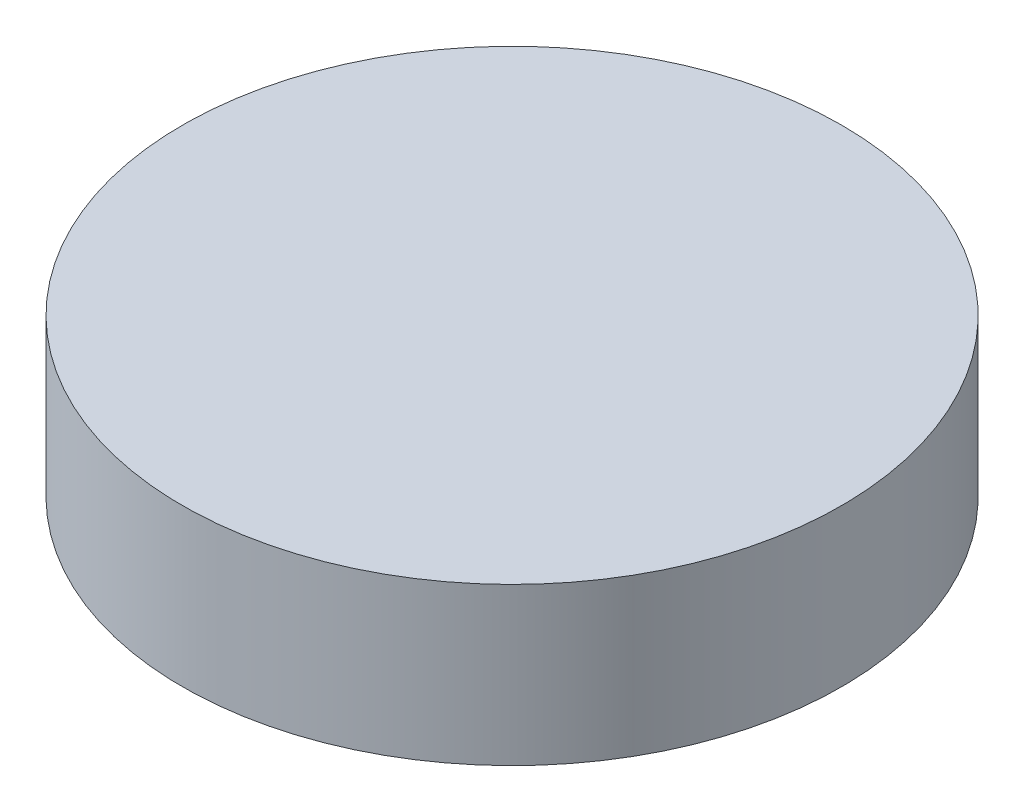
SolidWorks part; units mm, degrees
ref_plane "前视基准面" through (0, 0, 0) normal (0, 0, 1) x (1, 0, 0)
ref_plane "上视基准面" through (0, 0, 0) normal (0, 1, 0) x (1, 0, 0)
ref_plane "右视基准面" through (0, 0, 0) normal (1, 0, 0) x (0, 0, -1)
other "Configuration Table"
sketch "草图1" plane through (0, 0, 0) normal (0, 0, 1) x (1, 0, 0)
  line L0 (0, 0) -> (10.5, 0)
  line L1 (10.5, 0) -> (10.5, 5)
  line L2 (10.5, 5) -> (0, 5)
  line L3 (0, 5) -> (0, 0)
  line L4 (0, 0) -> (0, 5) construction
  dimension "radius" = 10.5
  dimension "height" = 5
revolve "Revolve" add sketch "草图1" angle 360 about L4
